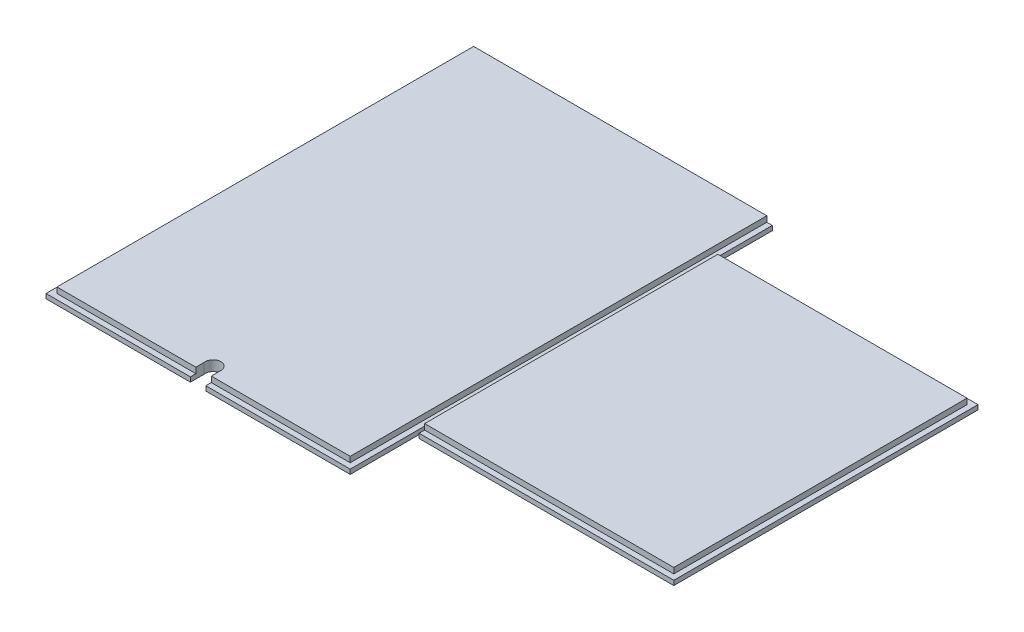
SolidWorks part; units mm, degrees
ref_plane "Alzado" through (0, 0, 0) normal (0, 0, 1) x (1, 0, 0)
ref_plane "Planta" through (0, 0, 0) normal (0, 1, 0) x (1, 0, 0)
ref_plane "Vista lateral" through (0, 0, 0) normal (1, 0, 0) x (0, 0, -1)
sketch "Croquis1" plane through (0, 0, 0) normal (0, 1, 0) x (1, 0, 0)
  line L1 (-57.745, 49.8873) -> (31.255, 49.8873)
  line L2 (-57.745, 49.8873) -> (-57.745, -73.6127)
  line L3 (-57.745, -73.6127) -> (31.255, -73.6127)
  line L4 (31.255, 49.8873) -> (31.255, -73.6127)
  line L5 (32.2556, 34.5595) -> (106.7556, 34.5595)
  line L6 (32.2556, 34.5595) -> (32.2556, -54.4405)
  line L7 (32.2556, -54.4405) -> (106.7556, -54.4405)
  line L8 (106.7556, 34.5595) -> (106.7556, -54.4405)
  dimension "D1" = 123.5
  dimension "D2" = 89
  dimension "D3" = 89
  dimension "D4" = 74.5
extrude "Saliente-Extruir1" add sketch "Croquis1" along normal blind 3
sketch "Croquis2" plane through (0, 3, 0) normal (0, 1, 0) x (1, 0, 0)
  line L0 (-57.745, 49.8873) -> (-57.745, -73.6127)
  line L1 (-57.745, -73.6127) -> (31.255, -73.6127)
  line L2 (31.255, -73.6127) -> (31.255, 49.8873)
  line L3 (31.255, 49.8873) -> (29.655, 49.8873)
  line L4 (29.655, 49.8873) -> (29.655, -72.0127)
  line L5 (29.655, -72.0127) -> (-56.145, -72.0127)
  line L6 (-56.145, -72.0127) -> (-56.145, 49.8873)
  line L7 (-56.145, 49.8873) -> (-57.745, 49.8873)
  line L8 (31.255, -73.6127) -> (31.255, 49.8873) construction
  line L9 (-57.745, 49.8873) -> (-57.745, -73.6127) construction
  line L10 (-57.745, -73.6127) -> (31.255, -73.6127) construction
  line L11 (31.255, 49.8873) -> (-57.745, 49.8873) construction
  line L23 (32.2556, 34.5595) -> (106.7556, 34.5595)
  line L24 (106.7556, 34.5595) -> (106.7556, -54.4405)
  line L25 (106.7556, -54.4405) -> (32.2556, -54.4405)
  line L26 (32.2556, -54.4405) -> (32.2556, -52.8405)
  line L27 (32.2556, -52.8405) -> (105.1556, -52.8405)
  line L28 (105.1556, -52.8405) -> (105.1556, 32.9595)
  line L29 (105.1556, 32.9595) -> (32.2556, 32.9595)
  line L30 (32.2556, 32.9595) -> (32.2556, 34.5595)
  line L31 (32.2556, 34.5595) -> (32.2556, -54.4405) construction
  dimension "D1" = 1.6
  dimension "D2" = 1.6
  dimension "D3" = 1.6
  dimension "D4" = 1.6
  dimension "D5" = 1.6
  dimension "D6" = 1.6
extrude "Cortar-Extruir1" cut sketch "Croquis2" against normal blind 1.65 contours L24 L25 L26 L27 L28 L29 L30 L23 | L3 L4 L5 L6 L7 L0 L1 L2
sketch "Croquis3" plane through (0, 3, 0) normal (0, 1, 0) x (1, 0, 0)
  line L0 (-15.495, -73.6127) -> (-15.495, -69.6127)
  line L1 (-10.995, -73.6127) -> (-10.995, -69.6127)
  line L2 (-57.745, -73.6127) -> (31.255, -73.6127) construction
  line L3 (-13.245, -73.6127) -> (-13.245, 47.7634) construction
  line L4 (-10.995, -73.6127) -> (-15.495, -73.6127)
  arc A0 (-15.495, -69.6127) -> (-10.995, -69.6127) centre (-13.245, -69.2322) cw
  dimension "D1" = 4.5
  dimension "D2" = 4
extrude "Cortar-Extruir3" cut sketch "Croquis3" against normal blind 6
